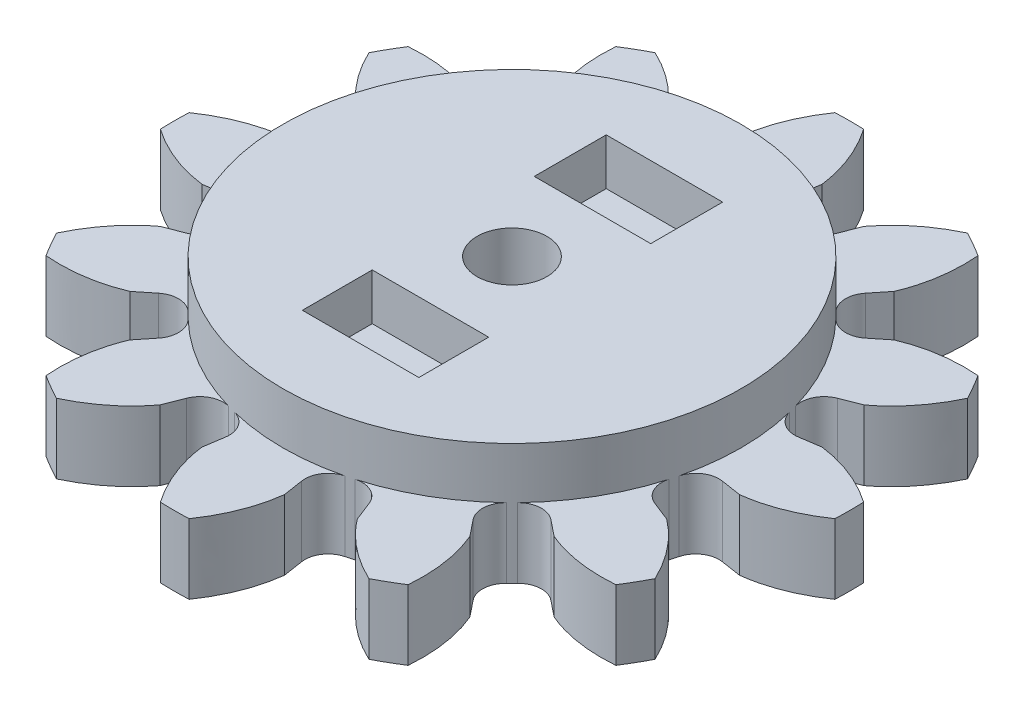
SolidWorks part; units mm, degrees
ref_plane "Front Plane" through (0, 0, 0) normal (0, 0, 1) x (1, 0, 0)
ref_plane "Top Plane" through (0, 0, 0) normal (0, 1, 0) x (1, 0, 0)
ref_plane "Right Plane" through (0, 0, 0) normal (1, 0, 0) x (0, 0, -1)
sketch "Sketch1" plane through (0, 0, 0) normal (0, 1, 0) x (1, 0, 0)
  circle A0 centre (0, 0) radius 9.835
  dimension "D1" = 19.67
extrude "Boss-Extrude1" add sketch "Sketch1" along normal blind 5.2
sketch "Sketch2" plane through (0, 0, 0) normal (0, -1, 0) x (1, 0, 0)
  line L0 (0, 0) -> (-1.7688, -11.539) construction
  line L1 (0, 0) -> (4.6808, -10.6943) construction
  line L2 (0, 0) -> (9.6771, -6.5293) construction
  line L3 (0, 0) -> (11.6689, -0.3371) construction
  line L4 (0, 0) -> (10.0379, 5.9598) construction
  line L5 (0, 0) -> (5.2903, 10.4063) construction
  line L6 (5.2903, 10.4063) -> (10.0379, 5.9598) construction
  line L7 (10.0379, 5.9598) -> (11.6689, -0.3371) construction
  line L8 (11.6689, -0.3371) -> (9.6771, -6.5293) construction
  line L9 (9.6771, -6.5293) -> (4.6808, -10.6943) construction
  line L10 (4.6808, -10.6943) -> (-1.7688, -11.539) construction
  line L11 (4.6808, -10.6943) -> (-1.2781, -13.3024) construction
  line L12 (9.6771, -6.5293) -> (2.4009, -17.3135) construction
  line L13 (11.6689, -0.3371) -> (11.1055, -19.8429) construction
  line L14 (10.0379, 5.9598) -> (23.3211, -16.4127) construction
  line L15 (5.2903, 10.4063) -> (34.2823, -4.3325) construction
  line L16 (0, 0) -> (0, -14.4935) construction
  line L17 (0, 0) -> (-1.6215, -12.3167) construction
  line L18 (-1.4902, -9.7214) -> (-1.7688, -11.539)
  line L19 (1.4902, -9.7214) -> (1.7688, -11.539)
  line L20 (-3.5702, -9.1641) -> (-4.2377, -10.8775)
  line L21 (-6.1513, -7.6739) -> (-7.3013, -9.1087)
  line L22 (-7.6739, -6.1513) -> (-9.1087, -7.3013)
  line L23 (-9.1641, -3.5702) -> (-10.8775, -4.2377)
  line L24 (-9.7214, -1.4902) -> (-11.539, -1.7688)
  line L25 (-9.7214, 1.4902) -> (-11.539, 1.7688)
  line L26 (-9.1641, 3.5702) -> (-10.8775, 4.2377)
  line L27 (-7.6739, 6.1513) -> (-9.1087, 7.3013)
  line L28 (-6.1513, 7.6739) -> (-7.3013, 9.1087)
  line L29 (-3.5702, 9.1641) -> (-4.2377, 10.8775)
  line L30 (-1.4902, 9.7214) -> (-1.7688, 11.539)
  line L31 (1.4902, 9.7214) -> (1.7688, 11.539)
  line L32 (3.5702, 9.1641) -> (4.2377, 10.8775)
  line L33 (6.1513, 7.6739) -> (7.3013, 9.1087)
  line L34 (7.6739, 6.1513) -> (9.1087, 7.3013)
  line L35 (9.1641, 3.5702) -> (10.8775, 4.2377)
  line L36 (9.7214, 1.4902) -> (11.539, 1.7688)
  line L37 (9.7214, -1.4902) -> (11.539, -1.7688)
  line L38 (9.1641, -3.5702) -> (10.8775, -4.2377)
  line L39 (7.6739, -6.1513) -> (9.1087, -7.3013)
  line L40 (6.1513, -7.6739) -> (7.3013, -9.1087)
  line L41 (3.5702, -9.1641) -> (4.2377, -10.8775)
  circle A0 centre (0, 0) radius 12.423 construction
  circle A1 centre (0, 0) radius 11.6738 construction
  circle A2 centre (0, 0) radius 14.4935 construction
  arc A3 (-0.6161, -14.4804) -> (0.6161, -14.4804) centre (0, 0) ccw
  circle A4 centre (0, 0) radius 9.835 construction
  arc A6 (-1.4902, -9.7214) -> (1.4902, -9.7214) centre (0, 0) ccw
  arc A7 (-7.7738, -12.2323) -> (-6.7066, -12.8484) centre (0, 0) ccw
  arc A8 (-6.1513, -7.6739) -> (-3.5702, -9.1641) centre (0, 0) ccw
  arc A9 (-12.8484, -6.7066) -> (-12.2323, -7.7738) centre (0, 0) ccw
  arc A10 (-9.1641, -3.5702) -> (-7.6739, -6.1513) centre (0, 0) ccw
  arc A11 (-14.4804, 0.6161) -> (-14.4804, -0.6161) centre (0, 0) ccw
  arc A12 (-9.7214, 1.4902) -> (-9.7214, -1.4902) centre (0, 0) ccw
  arc A13 (-12.2323, 7.7738) -> (-12.8484, 6.7066) centre (0, 0) ccw
  arc A14 (-7.6739, 6.1513) -> (-9.1641, 3.5702) centre (0, 0) ccw
  arc A15 (-6.7066, 12.8484) -> (-7.7738, 12.2323) centre (0, 0) ccw
  arc A16 (-3.5702, 9.1641) -> (-6.1513, 7.6739) centre (0, 0) ccw
  arc A17 (0.6161, 14.4804) -> (-0.6161, 14.4804) centre (0, 0) ccw
  arc A18 (1.4902, 9.7214) -> (-1.4902, 9.7214) centre (0, 0) ccw
  arc A19 (7.7738, 12.2323) -> (6.7066, 12.8484) centre (0, 0) ccw
  arc A20 (6.1513, 7.6739) -> (3.5702, 9.1641) centre (0, 0) ccw
  arc A21 (12.8484, 6.7066) -> (12.2323, 7.7738) centre (0, 0) ccw
  arc A22 (9.1641, 3.5702) -> (7.6739, 6.1513) centre (0, 0) ccw
  arc A23 (14.4804, -0.6161) -> (14.4804, 0.6161) centre (0, 0) ccw
  arc A24 (9.7214, -1.4902) -> (9.7214, 1.4902) centre (0, 0) ccw
  arc A25 (12.2323, -7.7738) -> (12.8484, -6.7066) centre (0, 0) ccw
  arc A26 (7.6739, -6.1513) -> (9.1641, -3.5702) centre (0, 0) ccw
  arc A27 (6.7066, -12.8484) -> (7.7738, -12.2323) centre (0, 0) ccw
  arc A28 (3.5702, -9.1641) -> (6.1513, -7.6739) centre (0, 0) ccw
  spline S0 degree 3 poles (-1.7688, -11.539) (-1.4669, -14.0067) (2.5403, -18.3849) (17.8608, -22.2544) (30.3923, -12.9832) (34.2823, -4.3325) knots 0 0 0 0 0.160421 0.360358 1 1 1 1 construction
  spline S1 degree 3 poles (-1.7688, -11.539) (-1.6418, -12.5956) (-1.2213, -13.6081) (-0.6161, -14.4804) knots 0 0 0 0 1 1 1 1
  spline S2 degree 3 poles (1.7688, -11.539) (1.6418, -12.5956) (1.2213, -13.6081) (0.6161, -14.4804) knots 0 0 0 0 1 1 1 1
  spline S3 degree 3 poles (-4.2377, -10.8775) (-4.8759, -11.729) (-5.7463, -12.3956) (-6.7066, -12.8484) knots 0 0 0 0 1 1 1 1
  spline S4 degree 3 poles (-7.3013, -9.1087) (-7.7197, -10.0872) (-7.8618, -11.1743) (-7.7738, -12.2323) knots 0 0 0 0 1 1 1 1
  spline S5 degree 3 poles (-9.1087, -7.3013) (-10.0872, -7.7197) (-11.1743, -7.8618) (-12.2323, -7.7738) knots 0 0 0 0 1 1 1 1
  spline S6 degree 3 poles (-10.8775, -4.2377) (-11.729, -4.8759) (-12.3956, -5.7463) (-12.8484, -6.7066) knots 0 0 0 0 1 1 1 1
  spline S7 degree 3 poles (-11.539, -1.7688) (-12.5956, -1.6418) (-13.6081, -1.2213) (-14.4804, -0.6161) knots 0 0 0 0 1 1 1 1
  spline S8 degree 3 poles (-11.539, 1.7688) (-12.5956, 1.6418) (-13.6081, 1.2213) (-14.4804, 0.6161) knots 0 0 0 0 1 1 1 1
  spline S9 degree 3 poles (-10.8775, 4.2377) (-11.729, 4.8759) (-12.3956, 5.7463) (-12.8484, 6.7066) knots 0 0 0 0 1 1 1 1
  spline S10 degree 3 poles (-9.1087, 7.3013) (-10.0872, 7.7197) (-11.1743, 7.8618) (-12.2323, 7.7738) knots 0 0 0 0 1 1 1 1
  spline S11 degree 3 poles (-7.3013, 9.1087) (-7.7197, 10.0872) (-7.8618, 11.1743) (-7.7738, 12.2323) knots 0 0 0 0 1 1 1 1
  spline S12 degree 3 poles (-4.2377, 10.8775) (-4.8759, 11.729) (-5.7463, 12.3956) (-6.7066, 12.8484) knots 0 0 0 0 1 1 1 1
  spline S13 degree 3 poles (-1.7688, 11.539) (-1.6418, 12.5956) (-1.2213, 13.6081) (-0.6161, 14.4804) knots 0 0 0 0 1 1 1 1
  spline S14 degree 3 poles (1.7688, 11.539) (1.6418, 12.5956) (1.2213, 13.6081) (0.6161, 14.4804) knots 0 0 0 0 1 1 1 1
  spline S15 degree 3 poles (4.2377, 10.8775) (4.8759, 11.729) (5.7463, 12.3956) (6.7066, 12.8484) knots 0 0 0 0 1 1 1 1
  spline S16 degree 3 poles (7.3013, 9.1087) (7.7197, 10.0872) (7.8618, 11.1743) (7.7738, 12.2323) knots 0 0 0 0 1 1 1 1
  spline S17 degree 3 poles (9.1087, 7.3013) (10.0872, 7.7197) (11.1743, 7.8618) (12.2323, 7.7738) knots 0 0 0 0 1 1 1 1
  spline S18 degree 3 poles (10.8775, 4.2377) (11.729, 4.8759) (12.3956, 5.7463) (12.8484, 6.7066) knots 0 0 0 0 1 1 1 1
  spline S19 degree 3 poles (11.539, 1.7688) (12.5956, 1.6418) (13.6081, 1.2213) (14.4804, 0.6161) knots 0 0 0 0 1 1 1 1
  spline S20 degree 3 poles (11.539, -1.7688) (12.5956, -1.6418) (13.6081, -1.2213) (14.4804, -0.6161) knots 0 0 0 0 1 1 1 1
  spline S21 degree 3 poles (10.8775, -4.2377) (11.729, -4.8759) (12.3956, -5.7463) (12.8484, -6.7066) knots 0 0 0 0 1 1 1 1
  spline S22 degree 3 poles (9.1087, -7.3013) (10.0872, -7.7197) (11.1743, -7.8618) (12.2323, -7.7738) knots 0 0 0 0 1 1 1 1
  spline S23 degree 3 poles (7.3013, -9.1087) (7.7197, -10.0872) (7.8618, -11.1743) (7.7738, -12.2323) knots 0 0 0 0 1 1 1 1
  spline S24 degree 3 poles (4.2377, -10.8775) (4.8759, -11.729) (5.7463, -12.3956) (6.7066, -12.8484) knots 0 0 0 0 1 1 1 1
  dimension "D1" = 23.3476
  dimension "D2" = 24.846
  dimension "D3" = 28.987
  dimension "D4" = 6.5047
  dimension "D5" = 13.0093
  dimension "D6" = 19.514
  dimension "D7" = 26.0187
  dimension "D8" = 32.5233
  dimension "D9" = 7.5
  dimension "D10" = 12
extrude "Boss-Extrude2" add sketch "Sketch2" against normal blind 3
fillet "Fillet1" radius 1 2 edges at (1.4902, 1.5, -9.7214) (-1.4902, 1.5, -9.7214)
fillet "Fillet2" radius 1 22 edges at (-9.7214, 1.5, 1.4902) (-7.6739, 1.5, 6.1513) (-9.1641, 1.5, 3.5702) (-6.1513, 1.5, 7.6739) (-3.5702, 1.5, 9.1641) (-1.4902, 1.5, 9.7214) (1.4902, 1.5, 9.7214) (3.5702, 1.5, 9.1641) (6.1513, 1.5, 7.6739) (7.6739, 1.5, 6.1513) (9.1641, 1.5, 3.5702) (9.7214, 1.5, 1.4902) (9.7214, 1.5, -1.4902) (9.1641, 1.5, -3.5702) (7.6739, 1.5, -6.1513) (6.1513, 1.5, -7.6739) (-9.7214, 1.5, -1.4902) (-9.1641, 1.5, -3.5702) (-6.1513, 1.5, -7.6739) (-7.6739, 1.5, -6.1513) (3.5702, 1.5, -9.1641) (-3.5702, 1.5, -9.1641)
sketch "Sketch3" plane through (0, 5.2, 0) normal (0, 1, 0) x (1, 0, 0)
  circle A0 centre (0, 0) radius 1.5
  dimension "D1" = 3
extrude "Cut-Extrude1" cut sketch "Sketch3" against normal through all
sketch "Sketch4" plane through (0, 5.2, 0) normal (0, 1, 0) x (1, 0, 0)
  line L0 (0, -5) -> (0, 5) construction
  line L2 (-2.5, 3.4555) -> (2.5, 3.4555)
  line L3 (-2.5, 3.4555) -> (-2.5, 6.5445)
  line L4 (-2.5, 6.5445) -> (2.5, 6.5445)
  line L5 (2.5, 3.4555) -> (2.5, 6.5445)
  line L6 (-2.5, 3.4555) -> (2.5, 6.5445) construction
  line L7 (-2.5, 6.5445) -> (2.5, 3.4555) construction
  line L8 (-2.5, -6.5) -> (2.5, -6.5)
  line L9 (-2.5, -6.5) -> (-2.5, -3.5)
  line L10 (-2.5, -3.5) -> (2.5, -3.5)
  line L11 (2.5, -6.5) -> (2.5, -3.5)
  line L12 (-2.5, -6.5) -> (2.5, -3.5) construction
  line L13 (-2.5, -3.5) -> (2.5, -6.5) construction
  point P5 (0, 0)
  dimension "D1" = 10
  dimension "D2" = 3.089
  dimension "D3" = 3
  dimension "D4" = 5
  dimension "D5" = 5
extrude "Cut-Extrude2" cut sketch "Sketch4" against normal blind 2
equation "\"value\"= 6.5046676"
equation "\"D4@Sketch2\"=\"value\""
equation "\"D5@Sketch2\"=2*\"value\""
equation "\"D6@Sketch2\"= 3*\"value\""
equation "\"D7@Sketch2\"=4*\"value\""
equation "\"D8@Sketch2\"=5*\"value\""
